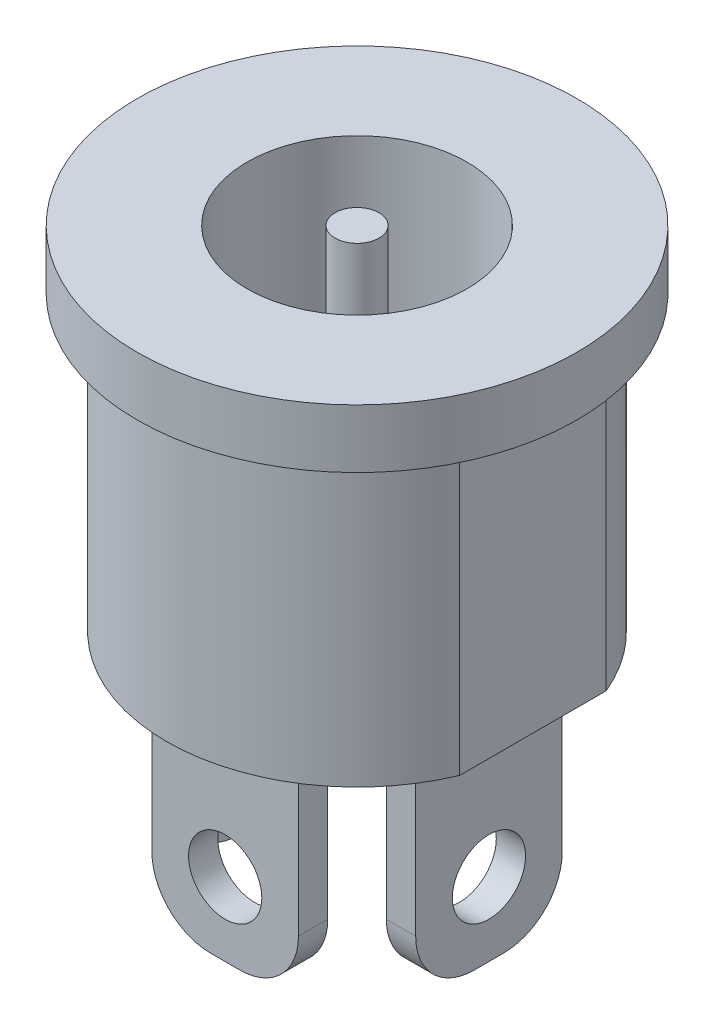
SolidWorks part; units mm, degrees
ref_plane "Alzado" through (0, 0, 0) normal (0, 0, 1) x (1, 0, 0)
ref_plane "Planta" through (0, 0, 0) normal (0, 1, 0) x (1, 0, 0)
ref_plane "Vista lateral" through (0, 0, 0) normal (1, 0, 0) x (0, 0, -1)
sketch "Croquis1" plane through (0, 0, 0) normal (0, 1, 0) x (1, 0, 0)
  line L2 (6, 2.5) -> (6, -2.5)
  line L3 (-6, 2.5) -> (-6, -2.5)
  arc A2 (-6, -2.5) -> (6, -2.5) centre (0, 0) ccw
  arc A3 (6, 2.5) -> (-6, 2.5) centre (0, 0) ccw
  dimension "D1" = 13
  dimension "D2" = 5
extrude "Saliente-Extruir1" add sketch "Croquis1" along normal blind 10
sketch "Croquis2" plane through (0, 10, 0) normal (0, 1, 0) x (1, 0, 0)
  circle A0 centre (0, 0) radius 7.5
  dimension "D1" = 15
extrude "Saliente-Extruir2" add sketch "Croquis2" along normal blind 2
sketch "Croquis3" plane through (0, 12, 0) normal (0, 1, 0) x (1, 0, 0)
  circle A0 centre (0, 0) radius 3.75
  circle A1 centre (0, 0) radius 0.75
  dimension "D1" = 1.5
  dimension "D2" = 7.5
extrude "Cortar-Extruir1" cut sketch "Croquis3" against normal blind 6.5
sketch "Croquis4" plane through (0, 0, 0) normal (0, -1, 0) x (1, 0, 0)
  line L1 (-4.5, 2.5) -> (-3.5, 2.5)
  line L2 (-4.5, 2.5) -> (-4.5, -2.5)
  line L3 (-4.5, -2.5) -> (-3.5, -2.5)
  line L4 (-3.5, 2.5) -> (-3.5, -2.5)
  line L5 (-4.5, 2.5) -> (-3.5, -2.5) construction
  line L6 (-4.5, -2.5) -> (-3.5, 2.5) construction
  line L7 (3.5, 2.5) -> (4.5, 2.5)
  line L8 (3.5, 2.5) -> (3.5, -2.5)
  line L9 (3.5, -2.5) -> (4.5, -2.5)
  line L10 (4.5, 2.5) -> (4.5, -2.5)
  line L11 (3.5, 2.5) -> (4.5, -2.5) construction
  line L12 (3.5, -2.5) -> (4.5, 2.5) construction
  line L13 (-2.5, 4.5) -> (2.5, 4.5)
  line L14 (-2.5, 4.5) -> (-2.5, 3.5)
  line L15 (-2.5, 3.5) -> (2.5, 3.5)
  line L16 (2.5, 4.5) -> (2.5, 3.5)
  line L17 (-2.5, 4.5) -> (2.5, 3.5) construction
  line L18 (-2.5, 3.5) -> (2.5, 4.5) construction
  point P0 (-4, 0)
  point P5 (4, 0)
  point P10 (0, 4)
  point P16 (0, 0)
  point P17 (0, 0)
  point P18 (0, 0)
  dimension "D1" = 5
  dimension "D2" = 4
  dimension "D3" = 4
  dimension "D4" = 1
  dimension "D5" = 4
extrude "Saliente-Extruir3" add sketch "Croquis4" along normal blind 7.5
sketch "Croquis5" plane through (-4.5, 0, 0) normal (-1, 0, 0) x (0, 0, 1)
  line L0 (2.5, -7.5) -> (-2.5, -7.5) construction
  line L1 (2.5, -7.5) -> (2.5, 0) construction
  circle A0 centre (0, -4.9977) radius 1.25
  dimension "D1" = 2.5
  dimension "D2" = 2.5023
  dimension "D3" = 2.5
extrude "Cortar-Extruir2" cut sketch "Croquis5" against normal up to surface (9 mm away) up to face at (4.5, -3.75, 0)
sketch "Croquis6" plane through (0, 0, 4.5) normal (0, 0, 1) x (1, 0, 0)
  line L0 (2.5, -7.5) -> (-2.5, -7.5) construction
  line L1 (2.5, -7.5) -> (2.5, 0) construction
  circle A0 centre (0, -5) radius 1.25
  dimension "D1" = 2.5
  dimension "D2" = 2.5
  dimension "D3" = 2.5
extrude "Cortar-Extruir3" cut sketch "Croquis6" against normal up to surface (1 mm away) up to face at (0, -3.75, 3.5)
fillet "Redondeo1" radius 2 6 edges at (-4, -7.5, -2.5) (-4, -7.5, 2.5) (-2.5, -7.5, 4) (2.5, -7.5, 4) (4, -7.5, -2.5) (4, -7.5, 2.5)
